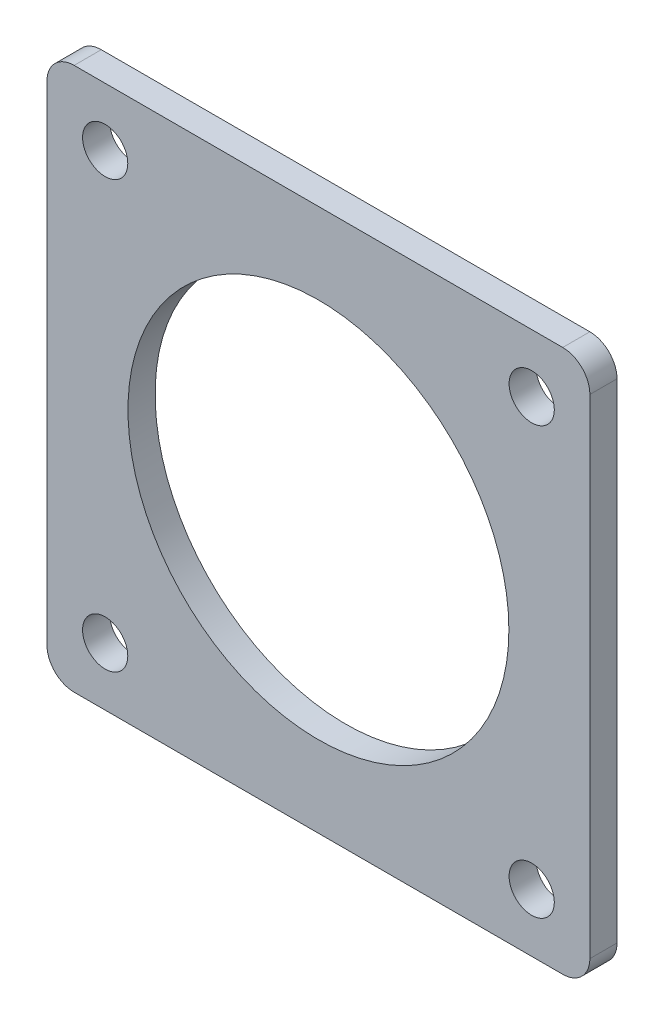
SolidWorks part; units mm, degrees
ref_plane "Front Plane" through (0, 0, 0) normal (0, 0, 1) x (1, 0, 0)
ref_plane "Top Plane" through (0, 0, 0) normal (0, 1, 0) x (1, 0, 0)
ref_plane "Right Plane" through (0, 0, 0) normal (1, 0, 0) x (0, 0, -1)
sketch "Sketch2" plane through (0, 0, 0) normal (0, 0, 1) x (1, 0, 0)
  line L2 (40.3115, 69.3437) -> (40.3115, 9.3437)
  line L4 (40.3115, 9.3437) -> (-19.6885, 9.3437)
  line L6 (-19.6885, 9.3437) -> (-19.6885, 69.3437)
  line L16 (-19.6885, 69.3437) -> (40.3115, 69.3437)
  circle A0 centre (33.8815, 15.7737) radius 2.5
  circle A1 centre (-13.2585, 15.7737) radius 2.5
  circle A2 centre (-13.2585, 62.9137) radius 2.5
  circle A3 centre (10.3115, 39.3437) radius 21.05
  circle A4 centre (33.8815, 62.9137) radius 2.5
  dimension "D3" = 42.1
  dimension "D1" = 60
  dimension "D2" = 60
extrude "Boss-Extrude1" add sketch "Sketch2" along normal blind 3 contours L2 L4 L6 L16
fillet "Fillet1" radius 3 4 edges at (-19.6885, 9.3437, 1.5) (40.3115, 9.3437, 1.5) (-19.6885, 69.3437, 1.5) (40.3115, 69.3437, 1.5)
